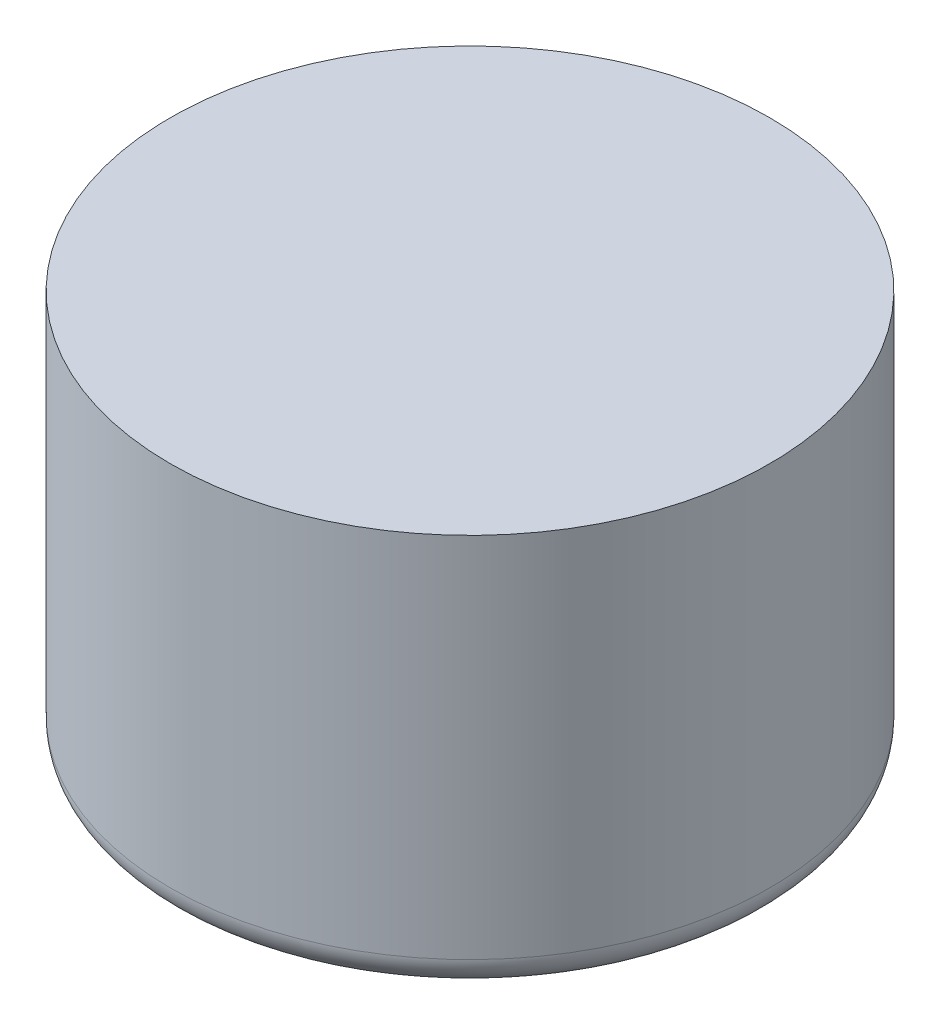
SolidWorks part; units mm, degrees
ref_plane "Front Plane" through (0, 0, 0) normal (0, 0, 1) x (1, 0, 0)
ref_plane "Top Plane" through (0, 0, 0) normal (0, 1, 0) x (1, 0, 0)
ref_plane "Right Plane" through (0, 0, 0) normal (1, 0, 0) x (0, 0, -1)
ref_axis "Centre Axis" through (0, -55, 0) along (0, 1, 0)
sketch "Sketch1" plane through (0, 0, 0) normal (0, 0, 1) x (1, 0, 0)
  line L0 (0, -55) -> (0, 55) construction
  line L1 (-24.2768, 32.258) -> (0, 32.258)
  line L2 (-24.2768, 32.258) -> (-24.2768, 2.5)
  line L3 (-21.7768, 0) -> (0, 0)
  line L4 (0, 15.9976) -> (0, -26.5891) construction
  line L5 (26.7045, 0) -> (-26.7045, 0) construction
  line L6 (0, 0) -> (0, 32.258)
  arc A0 (-24.2768, 2.5) -> (-21.7768, 0) centre (-21.7768, 2.5) ccw
  dimension "D1" = 2.5
  dimension "D2" = 48.5536
  dimension "D3" = 32.258
revolve "Revolve1" add sketch "Sketch1" angle 360 about axis through (0, -55, 0) along (0, 1, 0)
